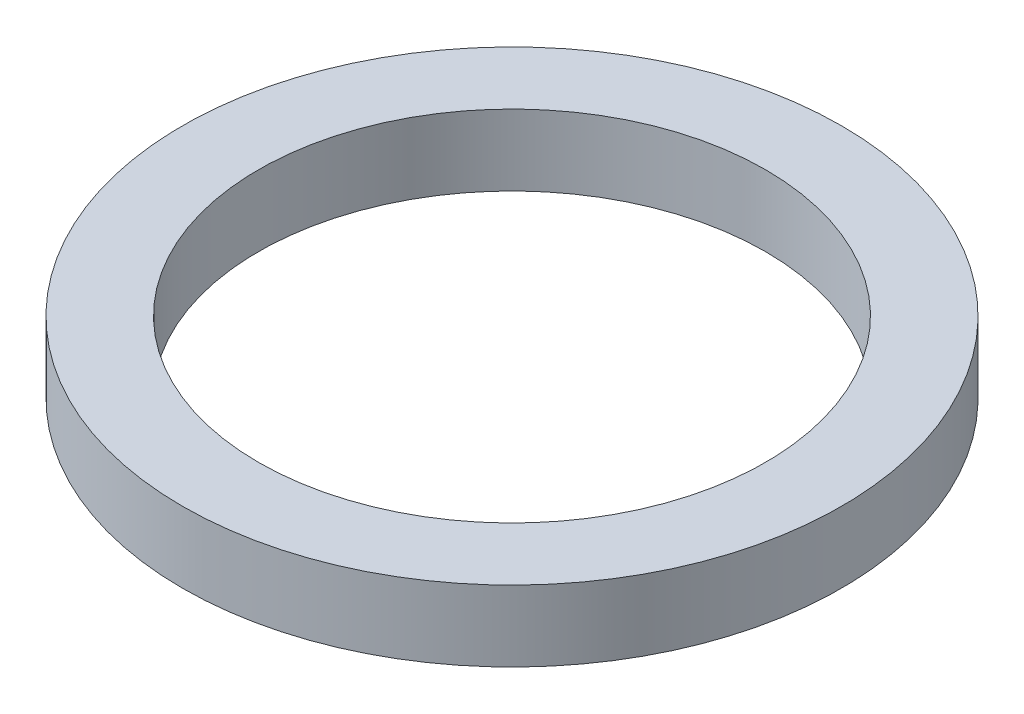
SolidWorks part; units mm, degrees
ref_plane "Alzado" through (0, 0, 0) normal (0, 0, 1) x (1, 0, 0)
ref_plane "Planta" through (0, 0, 0) normal (0, 1, 0) x (1, 0, 0)
ref_plane "Vista lateral" through (0, 0, 0) normal (1, 0, 0) x (0, 0, -1)
sketch "Croquis1" plane through (0, 0, 0) normal (0, 1, 0) x (1, 0, 0)
  circle A0 centre (0, 0) radius 32.5
  circle A1 centre (0, 0) radius 25
extrude "Saliente-Extruir1" add sketch "Croquis1" along normal blind 7
